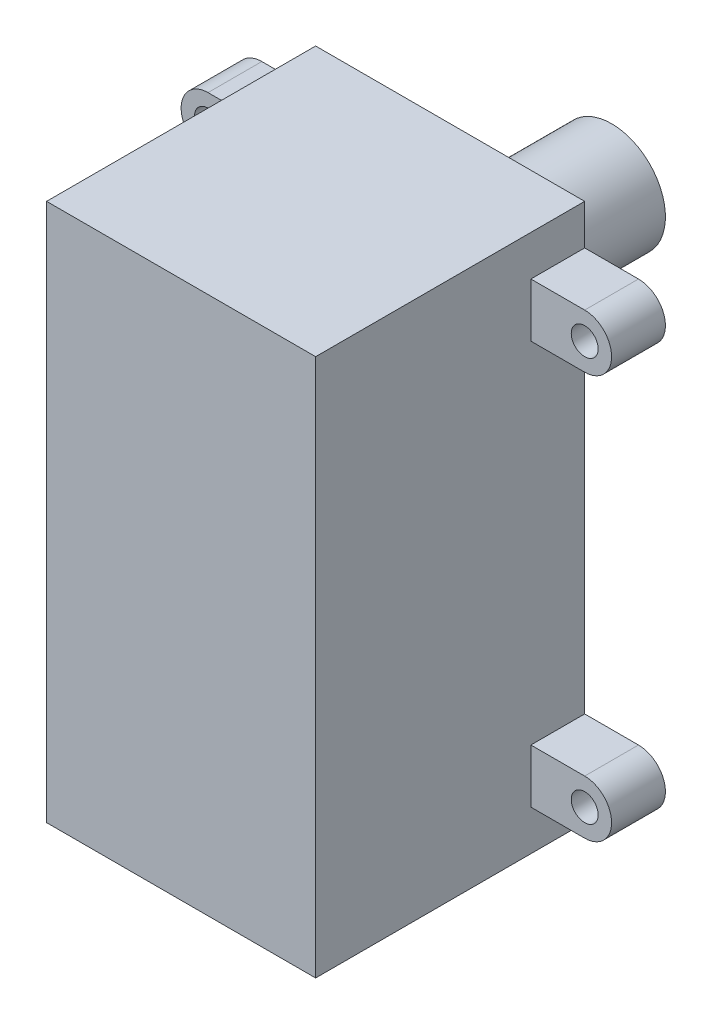
SolidWorks part; units mm, degrees
ref_plane "Front Plane" through (0, 0, 0) normal (1, 0, 0) x (0, 1, 0)
ref_plane "Top Plane" through (0, 0, 0) normal (0, 0, 1) x (0, 1, 0)
ref_plane "Right Plane" through (0, 0, 0) normal (0, 1, 0) x (-1, 0, 0)
sketch "Sketch1" plane through (0, 0, 0) normal (0, 0, 1) x (0, 1, 0)
  line L1 (-5, -46.7062) -> (95, -46.7062)
  line L2 (-5, -46.7062) -> (-5, 3.2938)
  line L3 (-5, 3.2938) -> (95, 3.2938)
  line L4 (95, -46.7062) -> (95, 3.2938)
  line L5 (-5, -46.7062) -> (95, 3.2938) construction
  line L6 (-5, 3.2938) -> (95, -46.7062) construction
  point P0 (45, -21.7062)
  dimension "D1" = 100
  dimension "D2" = 50
extrude "Boss-Extrude1" add sketch "Sketch1" along normal blind 50
sketch "Sketch2" plane through (0, 0, 0) normal (0, 0, -1) x (1, 0, 0)
  line L0 (-3.2938, -2.5) -> (-13.2938, -2.5)
  line L1 (-3.2938, -95) -> (-3.2938, 5) construction
  line L2 (-13.2938, -12.5) -> (-3.2938, -12.5)
  line L3 (-3.2938, -12.5) -> (-3.2938, -2.5)
  line L4 (-3.2938, 5) -> (46.7062, 5) construction
  line L5 (-3.2938, -45) -> (46.7062, -45) construction
  line L6 (46.7062, 5) -> (46.7062, -95) construction
  line L7 (-3.2938, -77.5) -> (-3.2938, -87.5)
  line L8 (-13.2938, -77.5) -> (-3.2938, -77.5)
  line L9 (-3.2938, -87.5) -> (-13.2938, -87.5)
  line L10 (21.7062, -45) -> (21.7062, 5) construction
  line L11 (46.7062, -87.5) -> (56.7062, -87.5)
  line L12 (56.7062, -77.5) -> (46.7062, -77.5)
  line L13 (46.7062, -77.5) -> (46.7062, -87.5)
  line L14 (46.7062, -12.5) -> (46.7062, -2.5)
  line L15 (56.7062, -12.5) -> (46.7062, -12.5)
  line L16 (46.7062, -2.5) -> (56.7062, -2.5)
  arc A0 (-13.2938, -2.5) -> (-13.2938, -12.5) centre (-13.2938, -7.5) ccw
  arc A1 (-13.2938, -87.5) -> (-13.2938, -77.5) centre (-13.2938, -82.5) cw
  circle A2 centre (-13.2938, -7.5) radius 2.5
  circle A3 centre (-13.2938, -82.5) radius 2.5
  circle A4 centre (56.7062, -82.5) radius 2.5
  circle A5 centre (56.7062, -7.5) radius 2.5
  arc A6 (56.7062, -87.5) -> (56.7062, -77.5) centre (56.7062, -82.5) ccw
  arc A7 (56.7062, -2.5) -> (56.7062, -12.5) centre (56.7062, -7.5) cw
  dimension "D2" = 10
  dimension "D4" = 5
  dimension "D1" = 10
  dimension "D3" = 7.5
extrude "Boss-Extrude2" add sketch "Sketch2" against normal blind 10
sketch "Sketch3" plane through (0, 0, 0) normal (0, 0, -1) x (1, 0, 0)
  line L0 (-3.2938, -45) -> (46.7062, -45) construction
  line L1 (-3.2938, -77.5) -> (-3.2938, -12.5) construction
  line L2 (46.7062, -12.5) -> (46.7062, -77.5) construction
  line L3 (46.7062, -45) -> (21.7062, -45) construction
  line L4 (21.7062, -45) -> (21.7062, -95) construction
  line L5 (46.7062, -95) -> (-3.2938, -95) construction
  circle A0 centre (21.7062, -70) radius 10
  dimension "D1" = 20
extrude "Boss-Extrude3" add sketch "Sketch3" along normal blind 30
